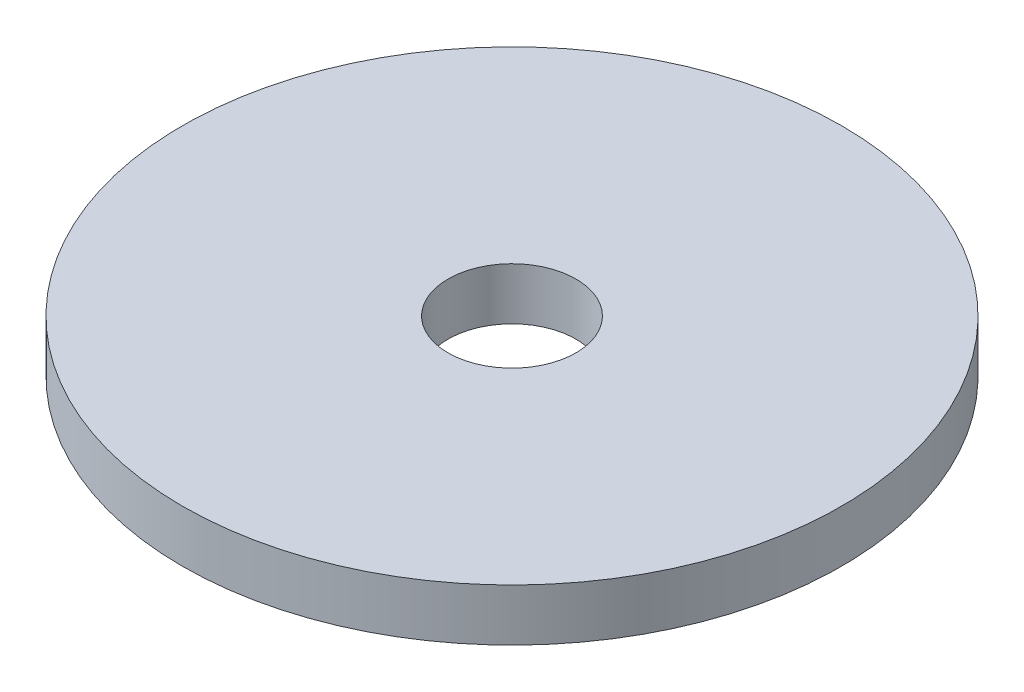
SolidWorks part; units mm, degrees
ref_plane "Front Plane" through (0, 0, 0) normal (0, 0, 1) x (1, 0, 0)
ref_plane "Top Plane" through (0, 0, 0) normal (0, 1, 0) x (1, 0, 0)
ref_plane "Right Plane" through (0, 0, 0) normal (1, 0, 0) x (0, 0, -1)
sketch "Sketch1" plane through (0, 0, 0) normal (0, 1, 0) x (1, 0, 0)
  circle A0 centre (0, 0) radius 17.4
  circle A1 centre (0, 0) radius 3.3782
  dimension "D1" = 34.8
  dimension "D2" = 6.7564
extrude "Boss-Extrude1" add sketch "Sketch1" along normal blind 2.75
